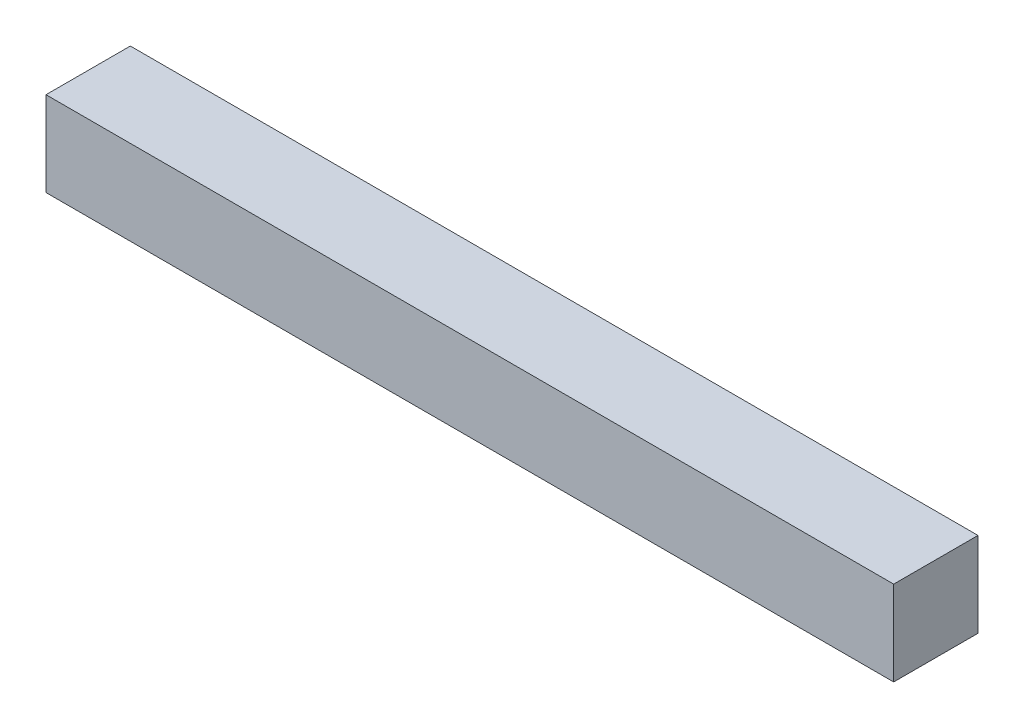
SolidWorks part; units mm, degrees
ref_plane "Front Plane" through (0, 0, 0) normal (0, 0, 1) x (1, 0, 0)
ref_plane "Top Plane" through (0, 0, 0) normal (0, 1, 0) x (1, 0, 0)
ref_plane "Right Plane" through (0, 0, 0) normal (1, 0, 0) x (0, 0, -1)
sketch "Sketch1" plane through (0, 0, 0) normal (0, 1, 0) x (1, 0, 0)
  line L1 (0, 0) -> (190.5, 0)
  line L2 (0, 0) -> (0, 18.9507)
  line L3 (0, 18.9507) -> (190.5, 18.9507)
  line L4 (190.5, 0) -> (190.5, 18.9507)
  dimension "D1" = 190.5
  dimension "D2" = 18.9507
extrude "Boss-Extrude1" add sketch "Sketch1" along normal blind 19.05
